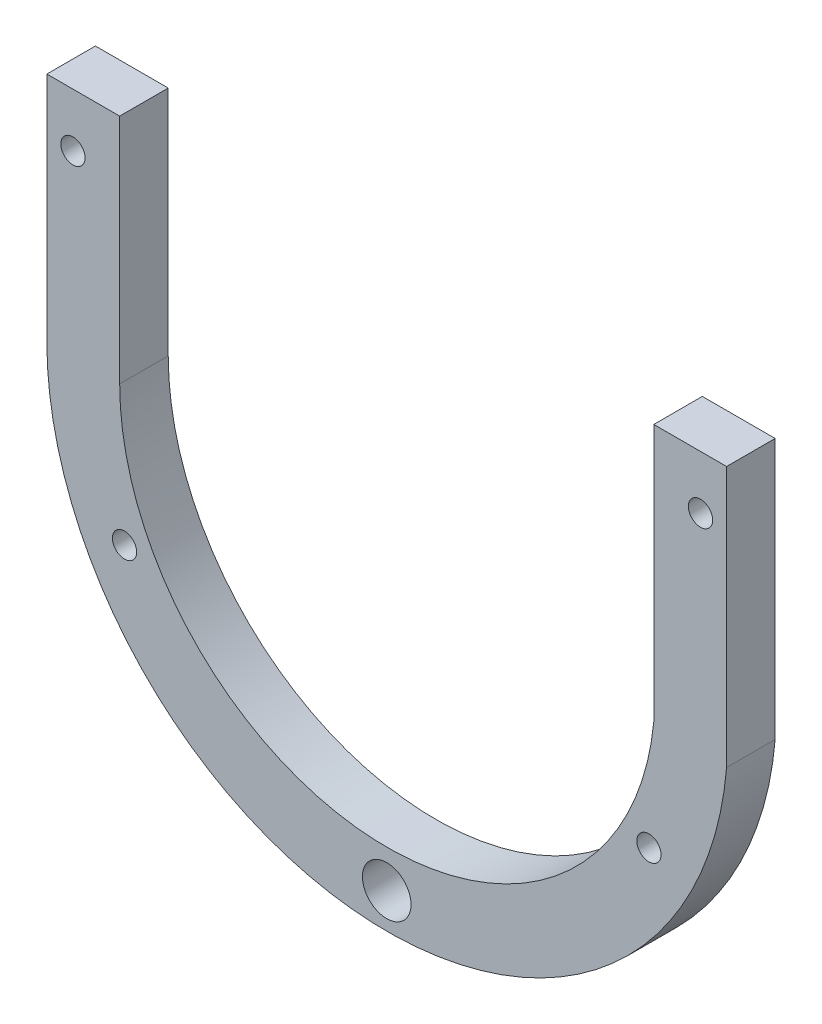
SolidWorks part; units mm, degrees
ref_plane "前视基准面" through (0, 0, 0) normal (0, 0, 1) x (1, 0, 0)
ref_plane "上视基准面" through (0, 0, 0) normal (0, 1, 0) x (1, 0, 0)
ref_plane "右视基准面" through (0, 0, 0) normal (1, 0, 0) x (0, 0, -1)
sketch "草图1" plane through (0, 0, 0) normal (0, 0, 1) x (1, 0, 0)
  line L1 (0, -3.7901) -> (200, -3.7901)
  line L2 (0, -3.7901) -> (0, 96.2099)
  line L3 (0, 96.2099) -> (200, 96.2099)
  line L4 (200, -3.7901) -> (200, 96.2099)
  dimension "D1" = 200
  dimension "D2" = 100
extrude "凸台-拉伸1" add sketch "草图1" along normal blind 8
ref_plane "基准面1" through (100, 0, 0) normal (1, 0, 0) x (0, 0, -1)
sketch "草图2" plane through (0, 0, 8) normal (0, 0, 1) x (1, 0, 0)
  line L0 (156, 96.2099) -> (156, 53.2595) construction
  line L1 (144, 96.2099) -> (144, 53.7971) construction
  line L2 (56, 57.9923) -> (56, 96.2099) construction
  line L3 (44, 57.9923) -> (44, 96.2099) construction
  line L4 (56, 96.2099) -> (44, 96.2099) construction
  line L5 (156, 96.2099) -> (144, 96.2099) construction
  line L6 (156, 96.2099) -> (156, 53.2595)
  line L7 (144, 96.2099) -> (144, 53.7971)
  line L8 (56, 57.9923) -> (56, 96.2099)
  line L9 (44, 57.9923) -> (44, 96.2099)
  line L10 (56, 96.2099) -> (44, 96.2099)
  line L11 (156, 96.2099) -> (144, 96.2099)
  arc A0 (44, 57.9923) -> (156, 53.2595) centre (100.1, 57.9923) ccw construction
  arc A1 (56, 57.9923) -> (144, 53.7971) centre (100.1, 57.9923) ccw construction
  arc A2 (44, 57.9923) -> (156, 53.2595) centre (100.1, 57.9923) ccw
  arc A3 (56, 57.9923) -> (144, 53.7971) centre (100.1, 57.9923) ccw
extrude "切除-拉伸1" cut sketch "草图2" against normal through all flip side to cut
sketch "草图3" plane through (0, 0, 13) normal (0, 0, 1) x (1, 0, 0)
  circle A0 centre (48.3, 87.3923) radius 2
  circle A1 centre (56.8, 35.3923) radius 2
  circle A2 centre (143.2, 35.3923) radius 2
  circle A3 centre (151.7, 87.3923) radius 2
  circle A4 centre (100, 7.6923) radius 4
  dimension "D1" = 8
extrude "切除-拉伸2" cut sketch "草图3" against normal through all
